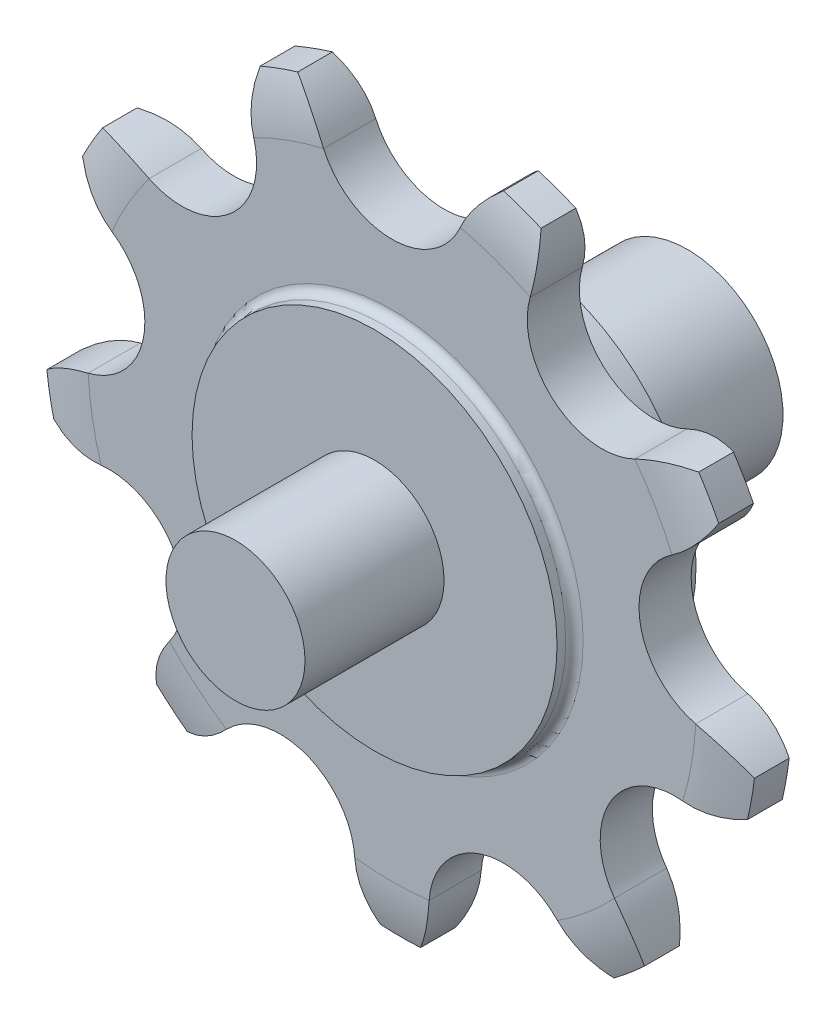
SolidWorks part; units mm, degrees
ref_plane "Front Plane" through (0, 0, 0) normal (0, 0, 1) x (1, 0, 0)
ref_plane "Top Plane" through (0, 0, 0) normal (0, 1, 0) x (1, 0, 0)
ref_plane "Right Plane" through (0, 0, 0) normal (1, 0, 0) x (0, 0, -1)
sketch "Sketch1" plane through (0, 0, 0) normal (0, 0, 1) x (1, 0, 0)
  line L0 (0, 0) -> (0, 24) construction
  line L28 (0, 0) -> (-8.2085, 22.5526) construction
  line L29 (0, 0) -> (8.2085, 22.5526) construction
  arc A0 (8.0792, 18.8408) -> (7.0114, 19.2637) centre (0, 0) ccw
  arc A1 (7.9516, 15.5891) -> (8.0792, 18.8408) centre (1.3889, 17.4749) ccw
  arc A2 (7.9516, 15.5891) -> (13.9715, 10.5379) centre (12.0844, 14.4016) ccw
  circle A3 centre (0, 0) radius 12.25 construction
  arc A4 (13.9715, 10.5379) -> (17.1517, 11.2281) centre (16.9682, 4.4022) cw
  circle A5 centre (0, 0) radius 20.5 construction
  circle A6 centre (0, 0) radius 17.5 construction
  arc A7 (17.1517, 11.2281) -> (17.7535, 10.25) centre (0, 0) cw
  arc A8 (18.2997, 9.2397) -> (17.7535, 10.25) centre (0, 0) ccw
  arc A9 (16.1118, 6.8308) -> (18.2997, 9.2397) centre (12.2966, 12.4938) ccw
  arc A10 (16.1118, 6.8308) -> (17.4764, -0.9083) centre (18.5144, 3.2646) ccw
  arc A11 (17.4764, -0.9083) -> (20.3562, -2.4236) centre (15.8281, -7.5347) cw
  arc A12 (20.3562, -2.4236) -> (20.1886, -3.5598) centre (0, 0) cw
  arc A13 (19.9575, -4.6848) -> (20.1886, -3.5598) centre (0, 0) ccw
  arc A14 (16.7331, -5.1238) -> (19.9575, -4.6848) centre (17.4506, 1.6667) ccw
  arc A15 (16.7331, -5.1238) -> (12.8039, -11.9294) centre (16.2813, -9.4) ccw
  arc A16 (12.8039, -11.9294) -> (14.0359, -14.9414) centre (7.2819, -15.946) cw
  arc A17 (14.0359, -14.9414) -> (13.1771, -15.7039) centre (0, 0) cw
  arc A18 (12.2771, -16.4172) -> (13.1771, -15.7039) centre (0, 0) ccw
  arc A19 (9.5248, -14.6809) -> (12.2771, -16.4172) centre (14.4393, -9.9402) ccw
  arc A20 (9.5248, -14.6809) -> (2.1403, -17.3686) centre (6.43, -17.6662) ccw
  arc A21 (2.1403, -17.3686) -> (1.148, -20.4678) centre (-4.6717, -16.896) cw
  arc A22 (1.148, -20.4678) -> (0, -20.5) centre (0, 0) cw
  arc A23 (-1.148, -20.4678) -> (0, -20.5) centre (0, 0) ccw
  arc A24 (-2.1403, -17.3686) -> (-1.148, -20.4678) centre (4.6717, -16.896) ccw
  arc A25 (-2.1403, -17.3686) -> (-9.5248, -14.6809) centre (-6.43, -17.6662) ccw
  arc A26 (-9.5248, -14.6809) -> (-12.2771, -16.4172) centre (-14.4393, -9.9402) cw
  arc A27 (-12.2771, -16.4172) -> (-13.1771, -15.7039) centre (0, 0) cw
  arc A28 (-14.0359, -14.9414) -> (-13.1771, -15.7039) centre (0, 0) ccw
  arc A29 (-12.8039, -11.9294) -> (-14.0359, -14.9414) centre (-7.2819, -15.946) ccw
  arc A30 (-12.8039, -11.9294) -> (-16.7331, -5.1238) centre (-16.2813, -9.4) ccw
  arc A31 (-16.7331, -5.1238) -> (-19.9575, -4.6848) centre (-17.4506, 1.6667) cw
  arc A32 (-19.9575, -4.6848) -> (-20.1886, -3.5598) centre (0, 0) cw
  arc A33 (-3.9292, 17.0532) -> (3.9292, 17.0532) centre (0, 18.8) ccw
  arc A34 (-3.9292, 17.0532) -> (-5.9217, 19.6261) centre (-10.1687, 14.2793) ccw
  arc A35 (3.9292, 17.0532) -> (5.9217, 19.6261) centre (10.1687, 14.2793) cw
  arc A36 (-5.9217, 19.6261) -> (-7.0114, 19.2637) centre (0, 0) ccw
  arc A37 (5.9217, 19.6261) -> (7.0114, 19.2637) centre (0, 0) cw
  arc A38 (-20.3562, -2.4236) -> (-20.1886, -3.5598) centre (0, 0) ccw
  arc A39 (-17.4764, -0.9083) -> (-20.3562, -2.4236) centre (-15.8281, -7.5347) ccw
  arc A40 (-17.4764, -0.9083) -> (-16.1118, 6.8308) centre (-18.5144, 3.2646) ccw
  arc A41 (-16.1118, 6.8308) -> (-18.2997, 9.2397) centre (-12.2966, 12.4938) cw
  arc A42 (-18.2997, 9.2397) -> (-17.7535, 10.25) centre (0, 0) cw
  arc A43 (-17.1517, 11.2281) -> (-17.7535, 10.25) centre (0, 0) ccw
  arc A44 (-13.9715, 10.5379) -> (-17.1517, 11.2281) centre (-16.9682, 4.4022) ccw
  arc A45 (-13.9715, 10.5379) -> (-7.9516, 15.5891) centre (-12.0844, 14.4016) ccw
  arc A46 (-7.9516, 15.5891) -> (-8.0792, 18.8408) centre (-1.3889, 17.4749) cw
  arc A47 (-8.0792, 18.8408) -> (-7.0114, 19.2637) centre (0, 0) cw
  circle A78 centre (0, 0) radius 7 construction
  circle A79 centre (0, 0) radius 6.25 construction
  circle A80 centre (0, 0) radius 4 construction
  circle A81 centre (0, 0) radius 3 construction
  point P81 (0, 0)
  dimension "D1" = 20
  dimension "D4" = 20
  dimension "D5" = 41
  dimension "D6" = 35
  dimension "D7" = 6.8283
  dimension "D8" = 6.8283
  dimension "D9" = 14
  dimension "D10" = 24.5
  dimension "D13" = 24
  dimension "D14" = 9
  dimension "D25" = 4.3
  dimension "D29" = 12.5
  dimension "D30" = 8
  dimension "D31" = 6
  dimension "D26" = 18.8
extrude "Boss-Extrude1" add sketch "Sketch1" along normal mid plane 3
sketch "Sketch2" plane through (0, 0, 0) normal (1, 0, 0) x (0, 0, -1)
  line L0 (0, 0) -> (0, -17.5) construction
  line L1 (0, 0) -> (0, 17.5) construction
  line L2 (0, -17.5) -> (-1.5, -17.5) construction
  line L3 (-1.5, -17.3686) -> (-1.5, -20.4678) construction
  line L4 (0, -17.5) -> (1.5, -17.5) construction
  line L5 (1.5, -20.4678) -> (1.5, -17.3686) construction
  line L6 (0, -17.5) -> (0, -20.5) construction
  line L8 (0, -20.5) -> (-1, -20.5) construction
  line L9 (-1.5, -17.5) -> (-1.5, -20.5)
  line L10 (-1.5, -20.5) -> (-1, -20.5)
  line L11 (0, 0) -> (-1.5, 0) construction
  line L13 (0, 0) -> (1.5, 0) construction
  arc A0 (-1.5, -17.5) -> (-1, -20.5) centre (7.75, -17.5) ccw
  dimension "D1" = 35
  dimension "D2" = 3
  dimension "D3" = 0.5
revolve "Cut-Revolve2" cut sketch "Sketch2" angle 360 about L11
mirror "Mirror1" about plane through (0, 0, 0) normal (0, 0, 1) of "Cut-Revolve2"
sketch "Sketch3" plane through (0, 0, 1.5) normal (0, 0, 1) x (1, 0, 0)
  circle A0 centre (0, 0) radius 10.5
  circle A1 centre (0, 0) radius 4 construction
  dimension "D1" = 21
extrude "Boss-Extrude2" add sketch "Sketch3" along normal blind 1
fillet "Fillet1" radius 0.5 1 edges at (10.5, 0, 1.5)
sketch "Sketch4" plane through (0, 0, -1.5) normal (0, 0, -1) x (-1, 0, 0)
  circle A0 centre (0, 0) radius 10.5
  circle A1 centre (0, 0) radius 4 construction
  dimension "D1" = 21
  dimension "D2" = 8
extrude "Boss-Extrude3" add sketch "Sketch4" along normal blind 4
fillet "Fillet2" radius 0.5 1 edges at (10.5, 0, -1.5)
sketch "Sketch5" plane through (0, 0, 2.5) normal (0, 0, 1) x (1, 0, 0)
  point P0 (0, 0)
sketch "Sketch6" plane through (0, 0, 2.5) normal (0, 0, 1) x (1, 0, 0)
  circle A0 centre (0, 0) radius 4 construction
  circle A1 centre (0, 0) radius 4
extrude "Boss-Extrude4" add sketch "Sketch6" along normal blind 8
sketch "Sketch7" plane through (0, 0, -5.5) normal (0, 0, -1) x (-1, 0, 0)
  circle A0 centre (0, 0) radius 5.5
  dimension "D1" = 11
extrude "Boss-Extrude5" add sketch "Sketch7" along normal blind 10
